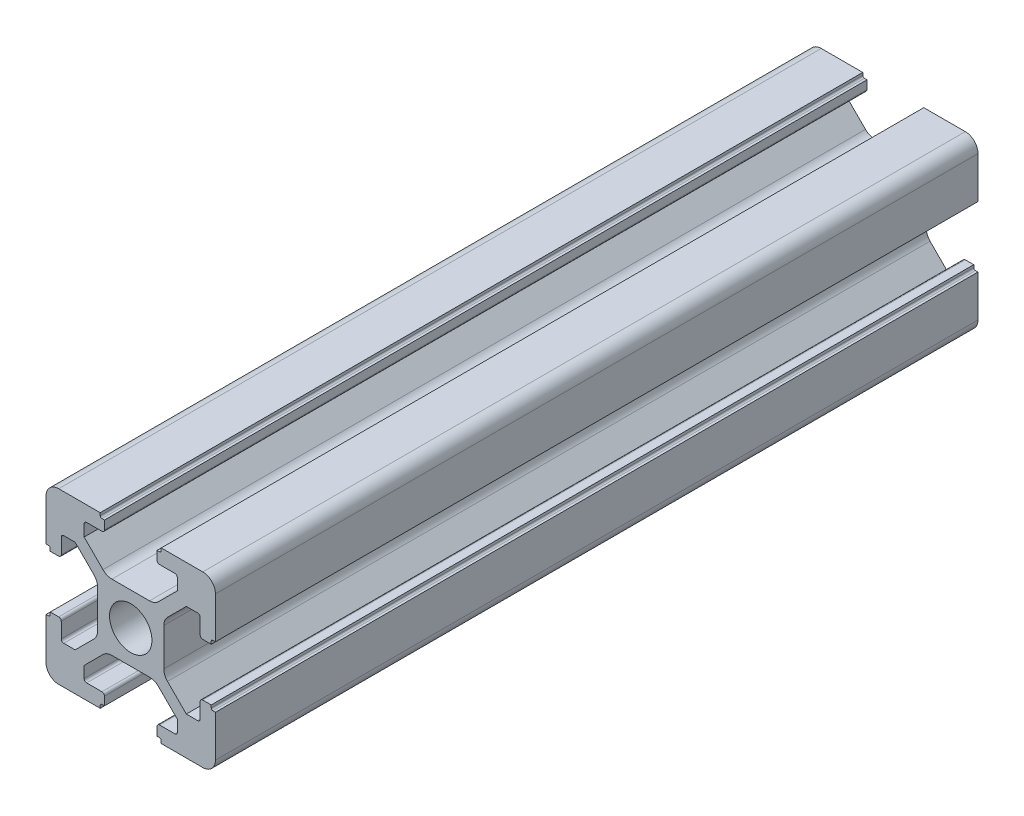
SolidWorks part; units mm, degrees
ref_plane "前视基准面" through (0, 0, 0) normal (0, 0, 1) x (1, 0, 0)
ref_plane "上视基准面" through (0, 0, 0) normal (0, 1, 0) x (1, 0, 0)
ref_plane "右视基准面" through (0, 0, 0) normal (1, 0, 0) x (0, 0, -1)
sketch "草图1" plane through (0, 0, 0) normal (0, 0, 1) x (1, 0, 0)
  line L0 (4.216, 3.2442) -> (6.4367, 5.4649)
  line L1 (6.4367, 5.4649) -> (7.7767, 5.4649)
  line L2 (8.0767, 5.1649) -> (8.0767, 3.3649)
  line L3 (8.3767, 3.0649) -> (9.3767, 3.0649)
  line L4 (9.3767, 3.0649) -> (9.3767, 3.3649)
  line L5 (9.5767, 3.5649) -> (9.8767, 3.5649)
  line L6 (9.8767, 3.5649) -> (9.8767, 8.4649)
  line L7 (8.3767, 9.9649) -> (3.4767, 9.9649)
  line L8 (3.4767, 9.9649) -> (3.4767, 9.6649)
  line L9 (3.2767, 9.4649) -> (2.9767, 9.4649)
  line L10 (2.9767, 9.4649) -> (2.9767, 8.4649)
  line L11 (3.2767, 8.1649) -> (5.0767, 8.1649)
  line L12 (5.3767, 7.8649) -> (5.3767, 6.5249)
  line L13 (5.3767, 6.5249) -> (3.156, 4.3042)
  line L14 (2.0953, 3.8649) -> (-2.342, 3.8649)
  line L15 (-3.4027, 4.3042) -> (-5.6233, 6.5249)
  line L16 (-5.6233, 6.5249) -> (-5.6233, 7.8649)
  line L17 (-5.3233, 8.1649) -> (-3.5233, 8.1649)
  line L18 (-3.2233, 8.4649) -> (-3.2233, 9.4649)
  line L19 (-3.2233, 9.4649) -> (-3.5233, 9.4649)
  line L20 (-3.7233, 9.6649) -> (-3.7233, 9.9649)
  line L21 (-3.7233, 9.9649) -> (-8.6233, 9.9649)
  line L22 (-10.1233, 8.4649) -> (-10.1233, 3.5649)
  line L23 (-10.1233, 3.5649) -> (-9.8233, 3.5649)
  line L24 (-9.6233, 3.3649) -> (-9.6233, 3.0649)
  line L25 (-9.6233, 3.0649) -> (-8.6233, 3.0649)
  line L26 (-8.3233, 3.3649) -> (-8.3233, 5.1649)
  line L27 (-8.0233, 5.4649) -> (-6.6833, 5.4649)
  line L28 (-6.6833, 5.4649) -> (-4.4627, 3.2442)
  line L29 (-4.0233, 2.1836) -> (-4.0233, -2.2538)
  line L30 (-4.4627, -3.3144) -> (-6.6833, -5.5351)
  line L31 (-6.6833, -5.5351) -> (-8.0233, -5.5351)
  line L32 (-8.3233, -5.2351) -> (-8.3233, -3.4351)
  line L33 (-8.6233, -3.1351) -> (-9.6233, -3.1351)
  line L34 (-9.6233, -3.1351) -> (-9.6233, -3.4351)
  line L35 (-9.8233, -3.6351) -> (-10.1233, -3.6351)
  line L36 (-10.1233, -3.6351) -> (-10.1233, -8.5351)
  line L37 (-8.6233, -10.0351) -> (-3.7233, -10.0351)
  line L38 (-3.7233, -10.0351) -> (-3.7233, -9.7351)
  line L39 (-3.5233, -9.5351) -> (-3.2233, -9.5351)
  line L40 (-3.2233, -9.5351) -> (-3.2233, -8.5351)
  line L41 (-3.5233, -8.2351) -> (-5.3233, -8.2351)
  line L42 (-5.6233, -7.9351) -> (-5.6233, -6.5951)
  line L43 (-5.6233, -6.5951) -> (-3.4027, -4.3744)
  line L44 (-2.342, -3.9351) -> (2.0953, -3.9351)
  line L45 (3.156, -4.3744) -> (5.3767, -6.5951)
  line L46 (5.3767, -6.5951) -> (5.3767, -7.9351)
  line L47 (5.0767, -8.2351) -> (3.2767, -8.2351)
  line L48 (2.9767, -8.5351) -> (2.9767, -9.5351)
  line L49 (2.9767, -9.5351) -> (3.2767, -9.5351)
  line L50 (3.4767, -9.7351) -> (3.4767, -10.0351)
  line L51 (3.4767, -10.0351) -> (8.3767, -10.0351)
  line L52 (9.8767, -8.5351) -> (9.8767, -3.6351)
  line L53 (9.8767, -3.6351) -> (9.5767, -3.6351)
  line L54 (9.3767, -3.4351) -> (9.3767, -3.1351)
  line L55 (9.3767, -3.1351) -> (8.3767, -3.1351)
  line L56 (8.0767, -3.4351) -> (8.0767, -5.2351)
  line L57 (7.7767, -5.5351) -> (6.4367, -5.5351)
  line L58 (6.4367, -5.5351) -> (4.216, -3.3144)
  line L59 (3.7767, -2.2538) -> (3.7767, 2.1836)
  circle A0 centre (-0.1233, -0.0351) radius 2.5
  arc A1 (8.0767, 5.1649) -> (7.7767, 5.4649) centre (7.7767, 5.1649) ccw
  arc A2 (8.0767, 3.3649) -> (8.3767, 3.0649) centre (8.3767, 3.3649) ccw
  arc A3 (9.5767, 3.5649) -> (9.3767, 3.3649) centre (9.5767, 3.3649) ccw
  arc A4 (9.8767, 8.4649) -> (8.3767, 9.9649) centre (8.3767, 8.4649) ccw
  arc A5 (3.2767, 9.4649) -> (3.4767, 9.6649) centre (3.2767, 9.6649) ccw
  arc A6 (2.9767, 8.4649) -> (3.2767, 8.1649) centre (3.2767, 8.4649) ccw
  arc A7 (5.3767, 7.8649) -> (5.0767, 8.1649) centre (5.0767, 7.8649) ccw
  arc A8 (2.0953, 3.8649) -> (3.156, 4.3042) centre (2.0953, 5.3649) ccw
  arc A9 (-3.4027, 4.3042) -> (-2.342, 3.8649) centre (-2.342, 5.3649) ccw
  arc A10 (-5.3233, 8.1649) -> (-5.6233, 7.8649) centre (-5.3233, 7.8649) ccw
  arc A11 (-3.5233, 8.1649) -> (-3.2233, 8.4649) centre (-3.5233, 8.4649) ccw
  arc A12 (-3.7233, 9.6649) -> (-3.5233, 9.4649) centre (-3.5233, 9.6649) ccw
  arc A13 (-8.6233, 9.9649) -> (-10.1233, 8.4649) centre (-8.6233, 8.4649) ccw
  arc A14 (-9.6233, 3.3649) -> (-9.8233, 3.5649) centre (-9.8233, 3.3649) ccw
  arc A15 (-8.6233, 3.0649) -> (-8.3233, 3.3649) centre (-8.6233, 3.3649) ccw
  arc A16 (-8.0233, 5.4649) -> (-8.3233, 5.1649) centre (-8.0233, 5.1649) ccw
  arc A17 (-4.0233, 2.1836) -> (-4.4627, 3.2442) centre (-5.5233, 2.1836) ccw
  arc A18 (-4.4627, -3.3144) -> (-4.0233, -2.2538) centre (-5.5233, -2.2538) ccw
  arc A19 (-8.3233, -5.2351) -> (-8.0233, -5.5351) centre (-8.0233, -5.2351) ccw
  arc A20 (-8.3233, -3.4351) -> (-8.6233, -3.1351) centre (-8.6233, -3.4351) ccw
  arc A21 (-9.8233, -3.6351) -> (-9.6233, -3.4351) centre (-9.8233, -3.4351) ccw
  arc A22 (-10.1233, -8.5351) -> (-8.6233, -10.0351) centre (-8.6233, -8.5351) ccw
  arc A23 (-3.5233, -9.5351) -> (-3.7233, -9.7351) centre (-3.5233, -9.7351) ccw
  arc A24 (-3.2233, -8.5351) -> (-3.5233, -8.2351) centre (-3.5233, -8.5351) ccw
  arc A25 (-5.6233, -7.9351) -> (-5.3233, -8.2351) centre (-5.3233, -7.9351) ccw
  arc A26 (-2.342, -3.9351) -> (-3.4027, -4.3744) centre (-2.342, -5.4351) ccw
  arc A27 (3.156, -4.3744) -> (2.0953, -3.9351) centre (2.0953, -5.4351) ccw
  arc A28 (5.0767, -8.2351) -> (5.3767, -7.9351) centre (5.0767, -7.9351) ccw
  arc A29 (3.2767, -8.2351) -> (2.9767, -8.5351) centre (3.2767, -8.5351) ccw
  arc A30 (3.4767, -9.7351) -> (3.2767, -9.5351) centre (3.2767, -9.7351) ccw
  arc A31 (8.3767, -10.0351) -> (9.8767, -8.5351) centre (8.3767, -8.5351) ccw
  arc A32 (9.3767, -3.4351) -> (9.5767, -3.6351) centre (9.5767, -3.4351) ccw
  arc A33 (8.3767, -3.1351) -> (8.0767, -3.4351) centre (8.3767, -3.4351) ccw
  arc A34 (7.7767, -5.5351) -> (8.0767, -5.2351) centre (7.7767, -5.2351) ccw
  arc A35 (3.7767, -2.2538) -> (4.216, -3.3144) centre (5.2767, -2.2538) ccw
  arc A36 (4.216, 3.2442) -> (3.7767, 2.1836) centre (5.2767, 2.1836) ccw
extrude "凸台-拉伸1" add sketch "草图1" along normal blind 90
